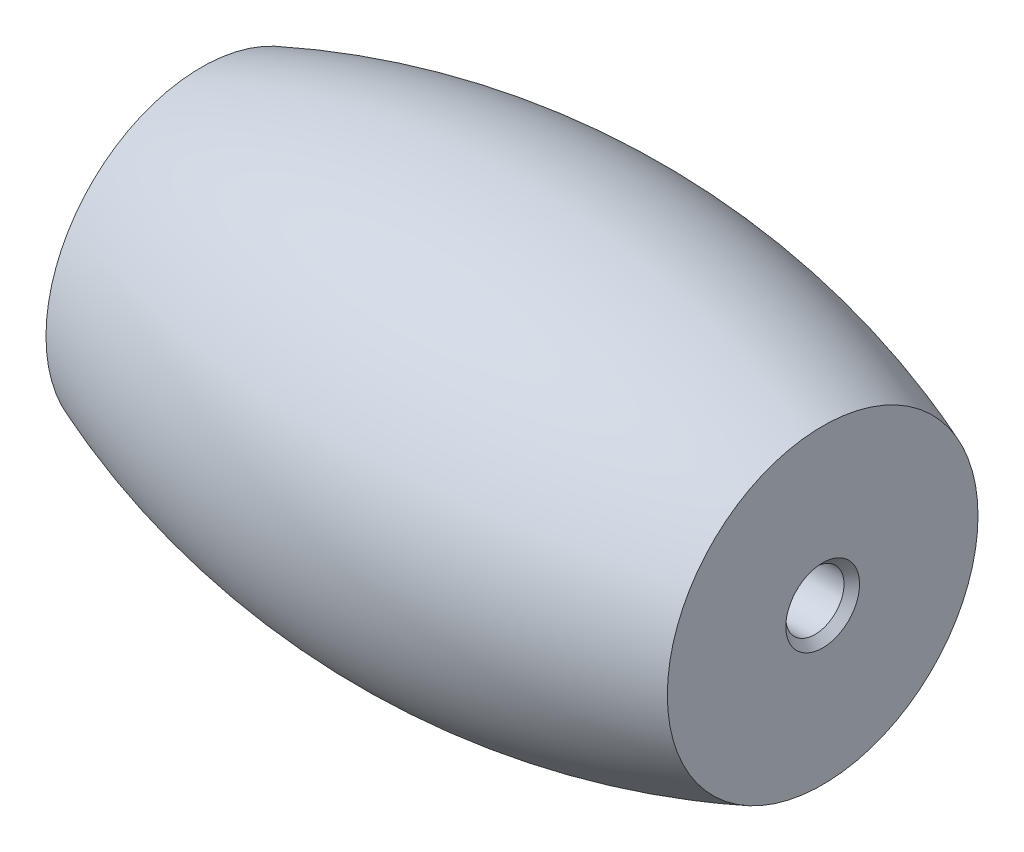
SolidWorks part; units mm, degrees
ref_plane "Alzado" through (0, 0, 0) normal (0, 0, 1) x (1, 0, 0)
ref_plane "Planta" through (0, 0, 0) normal (0, 1, 0) x (1, 0, 0)
ref_plane "Vista lateral" through (0, 0, 0) normal (1, 0, 0) x (0, 0, -1)
sketch "Croquis1" plane through (0, 0, 0) normal (0, 0, 1) x (1, 0, 0)
  line L5 (-8, 16.5798) -> (8, 16.5798) construction
  line L6 (-8, 20.5798) -> (-8, 16.5798)
  line L7 (-8, 16.5798) -> (8, 16.5798)
  line L8 (8, 16.5798) -> (8, 20.5798)
  arc A0 (8, 20.5798) -> (-8, 20.5798) centre (0, 0) ccw
revolve "Revolución1" add sketch "Croquis1" angle 360 about L5
sketch "Croquis2" plane through (-8, 0, 0) normal (-1, 0, 0) x (0, 0, 1)
  circle A0 centre (0, 16.5798) radius 0.75
  dimension "D1" = 1.5
extrude "Cortar-Extruir1" cut sketch "Croquis2" against normal up to surface (16 mm away) up to face at (8, 16.5798, 4)
chamfer "Chaflán1" distance 0.2 angle 45 2 edges at (8, 16.5798, 0.75) (-8, 16.5798, 0.75)
